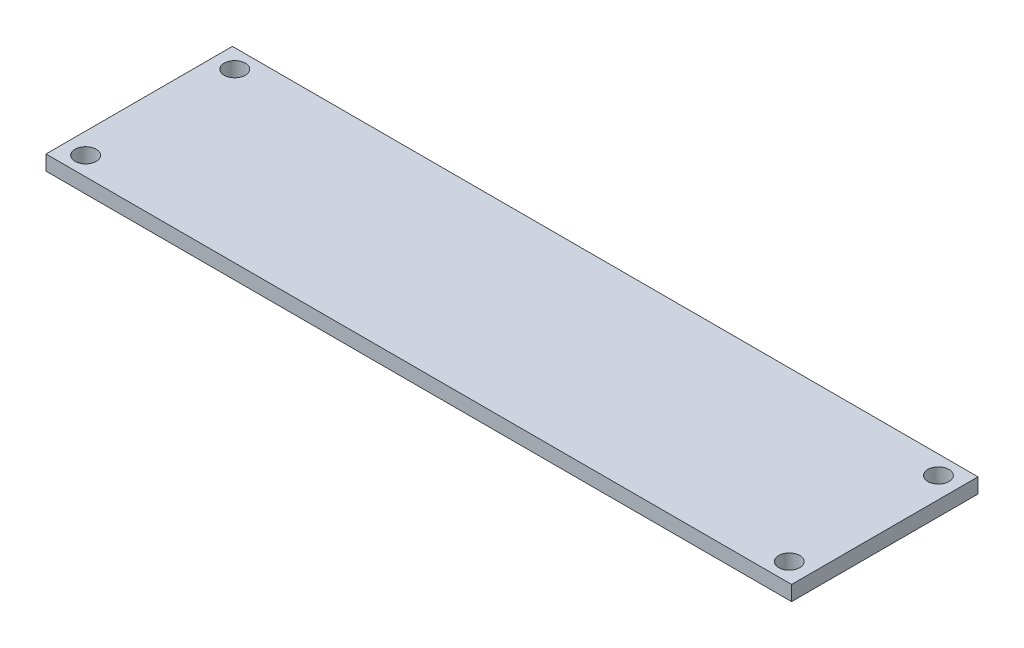
SolidWorks part; units mm, degrees
ref_plane "前视基准面" through (0, 0, 0) normal (0, 0, 1) x (1, 0, 0)
ref_plane "上视基准面" through (0, 0, 0) normal (0, 1, 0) x (1, 0, 0)
ref_plane "右视基准面" through (0, 0, 0) normal (1, 0, 0) x (0, 0, -1)
sketch "草图1" plane through (0, 0, 0) normal (0, 1, 0) x (1, 0, 0)
  line L0 (40, 20) -> (40, 0) construction
  line L1 (0, 0) -> (80, 0)
  line L2 (0, 0) -> (0, 20)
  line L3 (0, 20) -> (80, 20)
  line L4 (80, 0) -> (80, 20)
  line L5 (0, 10) -> (80, 10) construction
  circle A0 centre (2.25, 18) radius 1.133
  circle A1 centre (77.75, 18) radius 1.133
  circle A2 centre (77.75, 2) radius 1.133
  circle A3 centre (2.25, 2) radius 1.133
  dimension "D3" = 75.5
  dimension "D4" = 16
  dimension "D1" = 20
  dimension "D2" = 80
extrude "凸台-拉伸1" add sketch "草图1" along normal blind 1.6
